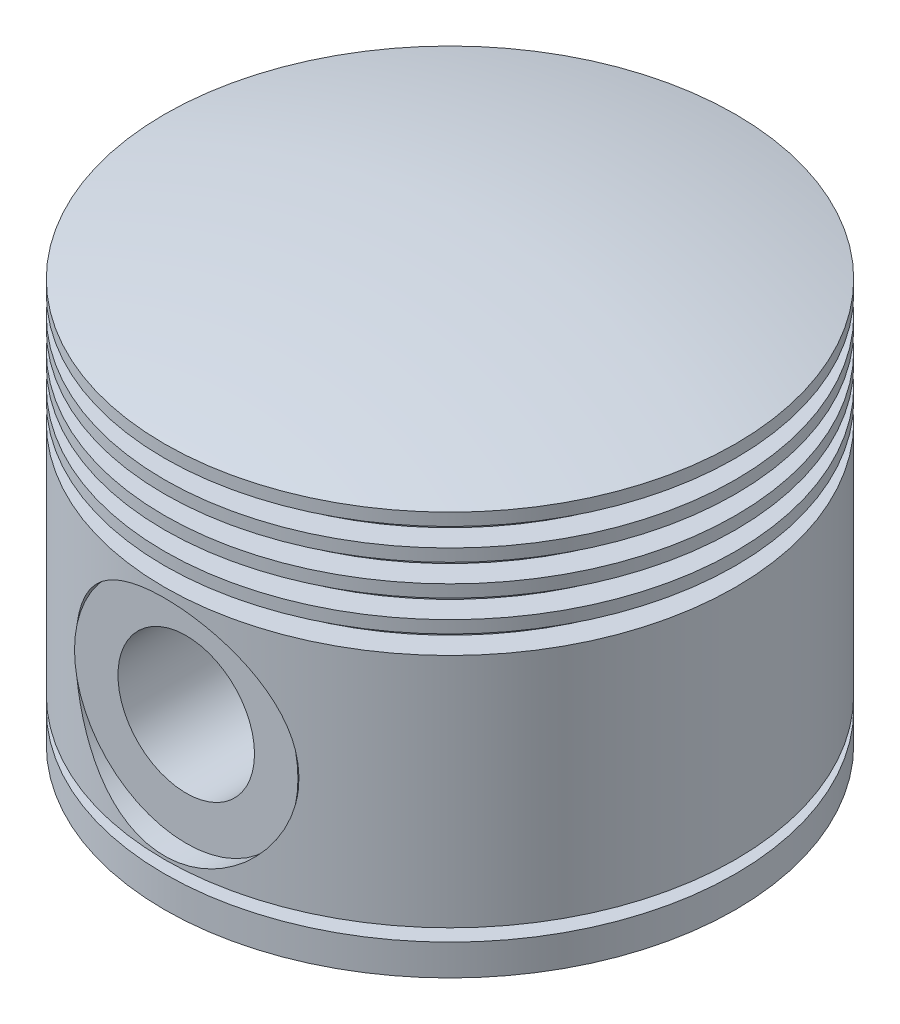
SolidWorks part; units mm, degrees
material "Alloy Steel"
ref_plane "Front Plane" through (0, 0, 0) normal (0, 0, 1) x (1, 0, 0)
ref_plane "Top Plane" through (0, 0, 0) normal (0, 1, 0) x (1, 0, 0)
ref_plane "Right Plane" through (0, 0, 0) normal (1, 0, 0) x (0, 0, -1)
sketch "Sketch1" plane through (0, 0, 0) normal (0, 0, 1) x (1, 0, 0)
  line L0 (37, 0) -> (46, 0)
  line L1 (46, 0) -> (46, 5)
  line L2 (46, 5) -> (42, 5)
  line L3 (42, 5) -> (42, 7)
  line L4 (42, 7) -> (46, 7)
  line L5 (46, 7) -> (46, 45)
  line L6 (46, 45) -> (42, 45)
  line L7 (42, 45) -> (42, 48)
  line L8 (42, 48) -> (46, 48)
  line L9 (46, 48) -> (46, 50)
  line L10 (46, 50) -> (42, 50)
  line L11 (42, 50) -> (42, 53)
  line L12 (42, 53) -> (46, 53)
  line L13 (46, 53) -> (46, 55)
  line L14 (46, 55) -> (42, 55)
  line L15 (42, 55) -> (42, 58)
  line L16 (42, 58) -> (46, 58)
  line L17 (46, 58) -> (46, 60)
  line L18 (46, 60) -> (42, 60)
  line L19 (42, 60) -> (42, 63)
  line L20 (42, 63) -> (46, 63)
  line L21 (46, 63) -> (46, 65)
  line L22 (46, 65) -> (0, 65) construction
  line L23 (0, 70.7779) -> (0, 62)
  line L24 (0, 62) -> (37, 62)
  line L25 (37, 62) -> (37, 0)
  arc A0 (46, 65) -> (0, 70.7779) centre (0, -115.2221) ccw
  dimension "D13" = 186
  dimension "D1" = 37
  dimension "D2" = 9
  dimension "D3" = 5
  dimension "D4" = 2
  dimension "4" = 4
  dimension "D5" = 3
  dimension "45" = 45
  dimension "D6" = 2
  dimension "D7" = 3
  dimension "D8" = 2
  dimension "D9" = 3
  dimension "D10" = 2
  dimension "D11" = 3
  dimension "D12" = 2
  dimension "62" = 62
revolve "Revolve1" add sketch "Sketch1" angle 360 about L23
hole_wizard "Ø12.0mm Dowel Hole3" positions "Sketch6" profile "Sketch7" hole size "Ø12.0" standard "ISO"
sketch "Sketch6" plane through (0, 0, 0) normal (0, 0, 1) x (1, 0, 0)
  point P0 (0, 25.5)
  dimension "D1" = 25.5
sketch "Sketch7" plane through (0, 25.5, 0) normal (1, 0, 0) x (0, 1, 0)
  line L0 (0, 0) -> (0, 46)
  line L1 (0, 46) -> (18, 46)
  line L2 (18, 46) -> (18, 0)
  line L5 (18, 0) -> (0, 0)
  line L11 (0, -6.35) -> (0, 107.95) construction
  dimension "Thru Hole Dia." = 36
  dimension "Thru Hole Depth" = 46
ref_plane "Plane1" through (0, 0, 25) normal (0, 0, 1) x (1, 0, 0)
sketch "Sketch8" plane through (0, 0, 25) normal (0, 0, 1) x (1, 0, 0)
  circle A0 centre (0, 25.5) radius 18 construction
  circle A1 centre (0, 25.5) radius 18
  circle A2 centre (0, 25.5) radius 11
  dimension "D1" = 22
extrude "Boss-Extrude1" add sketch "Sketch8" along normal blind 17.5
mirror "Mirror1" about plane through (0, 0, 0) normal (0, 0, 1) of "Boss-Extrude1", "Ø12.0mm Dowel Hole3"
